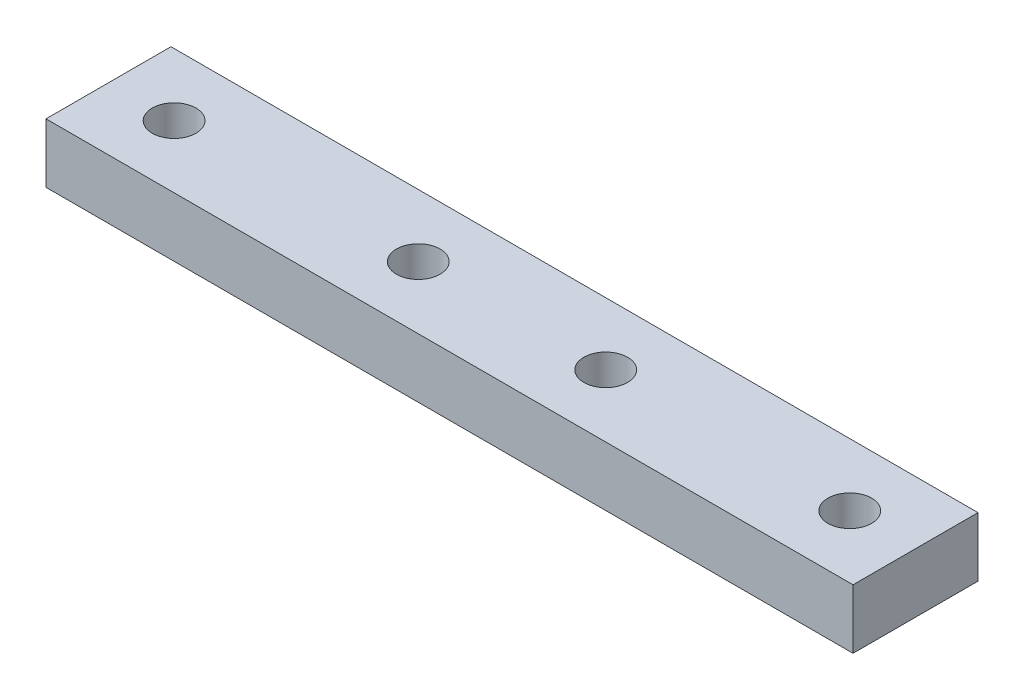
SolidWorks part; units mm, degrees
ref_plane "Front Plane" through (0, 0, 0) normal (0, 0, 1) x (1, 0, 0)
ref_plane "Top Plane" through (0, 0, 0) normal (0, 1, 0) x (1, 0, 0)
ref_plane "Right Plane" through (0, 0, 0) normal (1, 0, 0) x (0, 0, -1)
sketch " v  " plane through (0, 0, 0) normal (0, 1, 0) x (1, 0, 0)
  line L0 (0, -5) -> (0, 5) construction
  line L1 (-32.29, 5) -> (32.29, 5)
  line L2 (-32.29, 5) -> (-32.29, -5)
  line L3 (-32.29, -5) -> (32.29, -5)
  line L4 (32.29, 5) -> (32.29, -5)
  point P4 (0, 5)
  point P7 (32.29, 0)
  dimension "D1" = 64.58
  dimension "D2" = 10
extrude "Boss-Extrude1" add sketch " v  " along normal blind 4.75
sketch "Sketch2" plane through (0, 4.75, 0) normal (0, 1, 0) x (1, 0, 0)
  line L0 (32.29, 0) -> (-32.29, 0) construction
  line L1 (32.29, -5) -> (32.29, 5) construction
  line L2 (-32.29, 5) -> (-32.29, -5) construction
  circle A0 centre (-27.0395, 0) radius 1.75
  circle A1 centre (27.0305, 0) radius 1.75
  circle A4 centre (7.5, 0) radius 1.75
  circle A5 centre (-7.5, 0) radius 1.75
  dimension "D1" = 54.07
  dimension "D2" = 15
  dimension "D3" = 7.5
extrude "Cut-Extrude1" cut sketch "Sketch2" against normal through all
